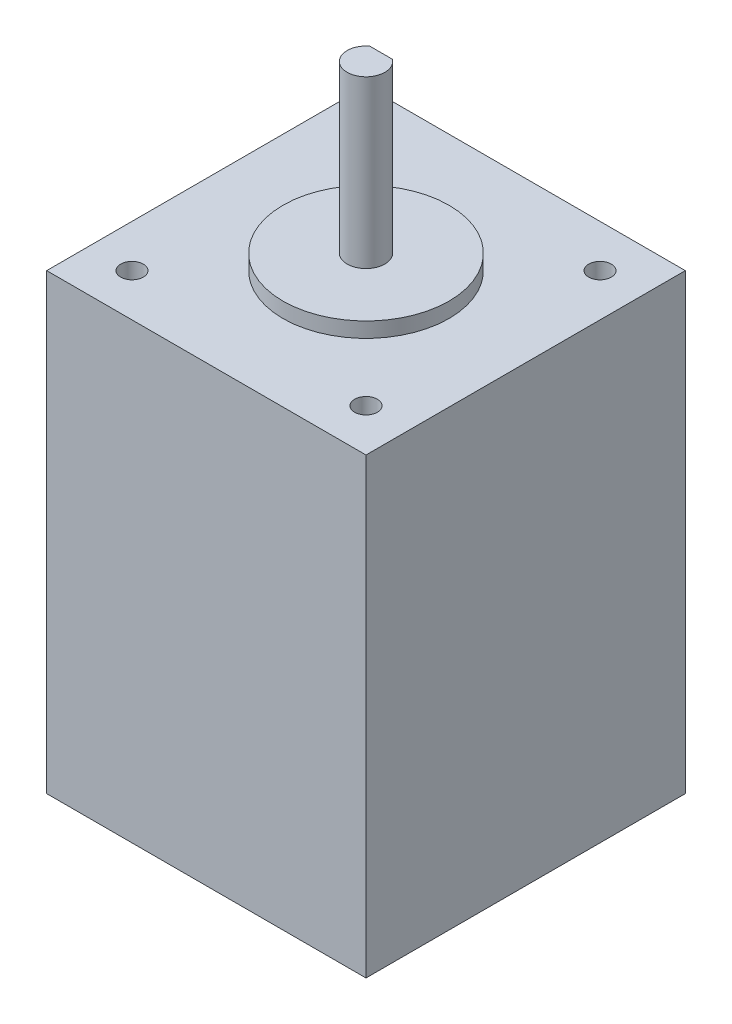
SolidWorks part; units mm, degrees
ref_plane "Спереди" through (0, 0, 0) normal (0, 0, 1) x (1, 0, 0)
ref_plane "Сверху" through (0, 0, 0) normal (0, 1, 0) x (1, 0, 0)
ref_plane "Справа" through (0, 0, 0) normal (1, 0, 0) x (0, 0, -1)
sketch "Эскиз1" plane through (0, 0, 0) normal (0, 1, 0) x (1, 0, 0)
  line L0 (21.15, 42.3) -> (21.15, -2.5503) construction
  line L1 (0, 0) -> (42.3, 0)
  line L2 (0, 0) -> (0, 42.3)
  line L3 (0, 42.3) -> (42.3, 42.3)
  line L4 (42.3, 0) -> (42.3, 42.3)
  line L5 (5.65, 42.3) -> (5.65, 0) construction
  line L6 (36.65, 42.3) -> (36.65, 0) construction
  line L7 (0, 36.65) -> (42.3, 36.65) construction
  line L8 (0, 5.65) -> (42.3, 5.65) construction
  line L9 (0, 21.15) -> (42.3, 21.15) construction
  circle A0 centre (5.65, 36.65) radius 1.5
  circle A1 centre (36.65, 36.65) radius 1.5
  circle A2 centre (36.65, 5.65) radius 1.5
  circle A3 centre (5.65, 5.65) radius 1.5
  point P25 (0, 0)
  point P26 (34.3852, 29.3726)
  point P27 (8.0027, 29.3726)
  point P28 (8.3545, 12.9274)
  point P29 (36.8476, 12.9274)
  point P30 (37.1994, 36.65)
  point P31 (5.0127, 5.65)
  point P32 (5.0127, 36.65)
  point P33 (5.65, 5.65)
  point P34 (5.65, 36.65)
  point P35 (36.65, 36.65)
  point P36 (36.65, 36.65)
  dimension "D3" = 3
  dimension "D1" = 42.3
  dimension "D2" = 42.3
  dimension "D4" = 31
  dimension "D5" = 31
extrude "Бобышка-Вытянуть1" add sketch "Эскиз1" along normal blind 60
sketch "Эскиз2" plane through (0, 60, 0) normal (0, 1, 0) x (1, 0, 0)
  line L0 (0, 21.15) -> (42.3, 21.15) construction
  line L1 (0, 42.3) -> (0, 0) construction
  line L2 (42.3, 0) -> (42.3, 42.3) construction
  line L3 (21.15, 42.3) -> (21.15, 0) construction
  line L4 (42.3, 42.3) -> (0, 42.3) construction
  line L5 (0, 0) -> (42.3, 0) construction
  circle A0 centre (21.15, 21.15) radius 11
  dimension "D1" = 22
extrude "Бобышка-Вытянуть2" add sketch "Эскиз2" along normal blind 2
sketch "Эскиз3" plane through (0, 62, 0) normal (0, 1, 0) x (1, 0, 0)
  circle A0 centre (21.15, 21.15) radius 2.5
  dimension "D1" = 5
extrude "Бобышка-Вытянуть3" add sketch "Эскиз3" along normal blind 22
sketch "Эскиз4" plane through (0, 84, 0) normal (0, 1, 0) x (1, 0, 0)
  line L0 (18.65, 18.65) -> (23.65, 18.65) construction
  line L1 (18.65, 23.65) -> (23.65, 23.65)
  line L2 (18.65, 23.65) -> (18.65, 23.15)
  line L3 (18.65, 23.15) -> (23.65, 23.15)
  line L4 (23.65, 23.65) -> (23.65, 23.15)
  circle A0 centre (21.15, 21.15) radius 2.5 construction
  circle A1 centre (21.15, 21.15) radius 2.5 construction
  point P8 (0, 0)
  point P11 (0, 0)
  point P12 (23.65, 18.65)
  point P13 (18.65, 18.65)
  point P14 (23.65, 18.65)
  point P15 (0, 0)
  point P16 (0, 0)
  point P17 (0, 0)
  dimension "D1" = 4.5
extrude "Вырез-Вытянуть1" cut sketch "Эскиз4" against normal blind 20
